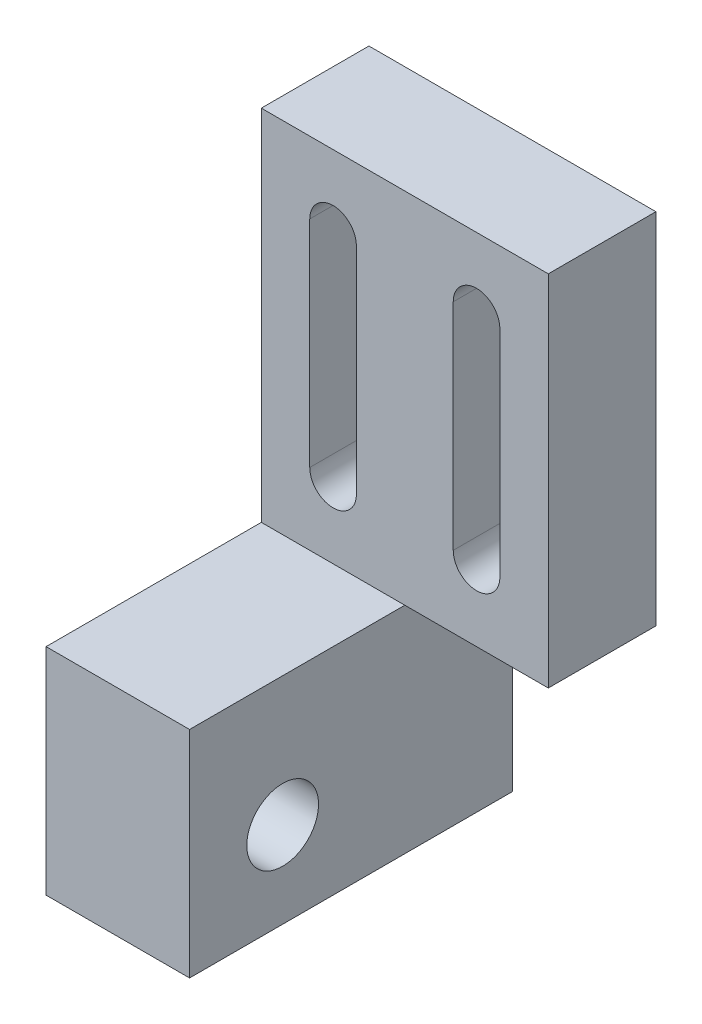
SolidWorks part; units mm, degrees
material "ABS"
ref_plane "前视基准面" through (0, 0, 0) normal (0, 0, 1) x (1, 0, 0)
ref_plane "上视基准面" through (0, 0, 0) normal (0, 1, 0) x (1, 0, 0)
ref_plane "右视基准面" through (0, 0, 0) normal (1, 0, 0) x (0, 0, -1)
other "Configuration Table"
sketch "草图1" plane through (0, 0, 0) normal (0, 0, 1) x (1, 0, 0)
  line L0 (-84.6, 0.47) -> (-68.7, 0.47) construction
  line L1 (-84.6, 6.47) -> (-80.6, 6.47)
  line L2 (-84.6, 6.47) -> (-84.6, 0.47)
  line L3 (-84.6, 0.47) -> (-80.6, 0.47)
  line L4 (-80.6, 6.47) -> (-80.6, 0.47)
  dimension "D1" = 6
  dimension "D2" = 4
extrude "凸台-拉伸1" add sketch "草图1" along normal blind 9
sketch "草图5" plane through (0, 0, 0) normal (0, 0, 1) x (1, 0, 0)
  line L1 (-84.6, 6.47) -> (-76.6, 6.47)
  line L2 (-84.6, 6.47) -> (-84.6, 16.47)
  line L3 (-84.6, 16.47) -> (-76.6, 16.47)
  line L4 (-76.6, 6.47) -> (-76.6, 16.47)
  dimension "D1" = 10
  dimension "D2" = 8
extrude "凸台-拉伸3" add sketch "草图5" along normal blind 3
sketch "草图7" plane through (-84.6, 0, 0) normal (-1, 0, 0) x (0, 0, 1)
  line L6 (0, 16.47) -> (0, 0.47)
  line L7 (0, 0.47) -> (9, 0.47)
  line L8 (9, 0.47) -> (9, 6.47)
  line L9 (9, 6.47) -> (3, 6.47)
  line L10 (3, 6.47) -> (3, 16.47)
  line L11 (3, 16.47) -> (0, 16.47)
  line L12 (0, 16.47) -> (0, 0.47)
  line L13 (0, 0.47) -> (9, 0.47)
  line L14 (9, 0.47) -> (9, 6.47)
  line L15 (9, 6.47) -> (3, 6.47)
  line L16 (3, 6.47) -> (3, 16.47)
  line L17 (3, 16.47) -> (0, 16.47)
  arc A0 (5.755, 3.6299) -> (7.055, 3.6299) centre (6.405, 2.87) ccw construction
  arc A1 (5.755, 3.6299) -> (7.055, 3.6299) centre (6.405, 2.87) ccw
  circle A2 centre (6.405, 2.87) radius 1
  dimension "D2" = 2
  dimension "D1" = 0
extrude "切除-拉伸4" cut sketch "草图7" against normal through all contours A1 A2
sketch "草图8" plane through (0, 0, 3) normal (0, 0, 1) x (1, 0, 0)
  line L0 (-82.6, 8.47) -> (-82.6, 14.47) construction
  line L1 (-83.25, 8.47) -> (-83.25, 14.47)
  line L2 (-81.95, 8.47) -> (-81.95, 14.47)
  line L3 (-78.6, 14.47) -> (-78.6, 8.47) construction
  line L4 (-77.95, 14.47) -> (-77.95, 8.47)
  line L5 (-79.25, 14.47) -> (-79.25, 8.47)
  line L6 (-80.6, 20.5485) -> (-80.6, 3.956) construction
  line L10 (-76.6, 6.47) -> (-76.6, 16.47) construction
  line L11 (-84.6, 16.47) -> (-84.6, 6.47) construction
  line L12 (-86.6279, 11.47) -> (-75.4887, 11.47) construction
  line L14 (-76.6, 16.47) -> (-84.6, 16.47) construction
  line L15 (-80.6, 6.47) -> (-76.6, 6.47) construction
  arc A0 (-83.25, 8.47) -> (-81.95, 8.47) centre (-82.6, 8.47) ccw
  arc A1 (-81.95, 14.47) -> (-83.25, 14.47) centre (-82.6, 14.47) ccw
  arc A2 (-77.95, 14.47) -> (-79.25, 14.47) centre (-78.6, 14.47) ccw
  arc A3 (-79.25, 8.47) -> (-77.95, 8.47) centre (-78.6, 8.47) ccw
  point P2 (-82.6, 11.47)
  point P8 (-78.6, 11.47)
  dimension "D1" = 1.3
  dimension "D2" = 2
  dimension "D3" = 4
extrude "切除-拉伸5" cut sketch "草图8" against normal through all
